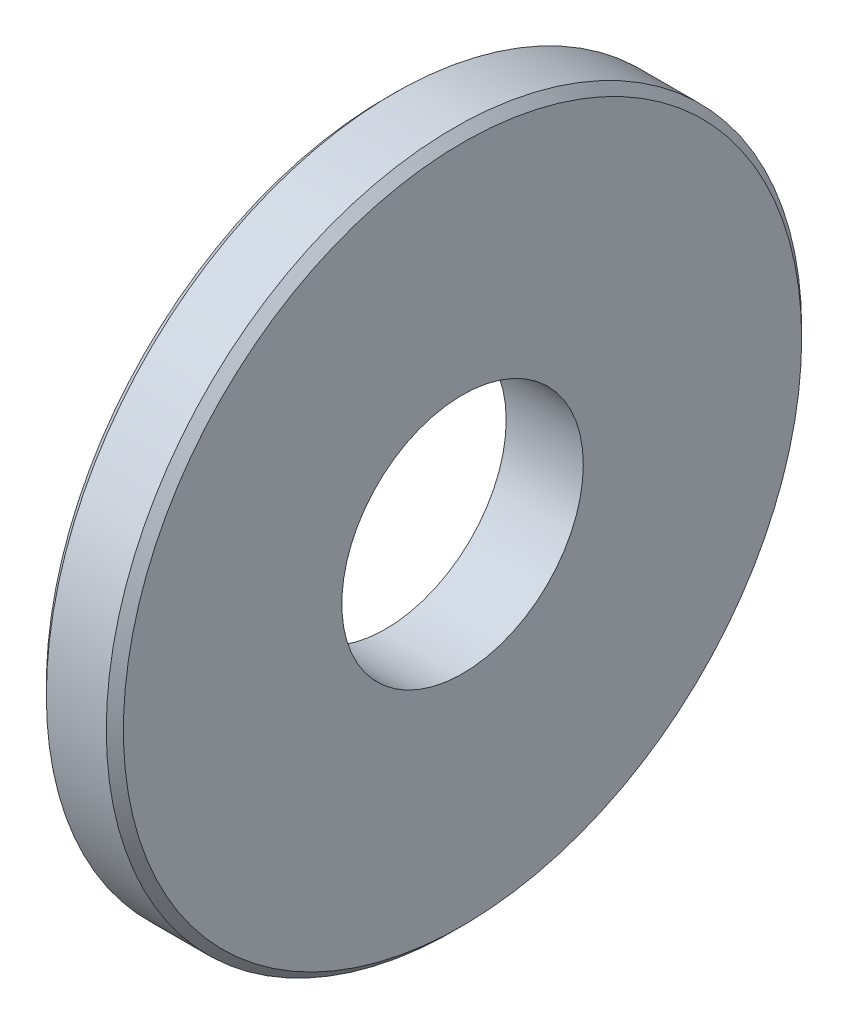
SolidWorks part; units mm, degrees
ref_plane "Front Plane" through (0, 0, 0) normal (0, 0, 1) x (1, 0, 0)
ref_plane "Top Plane" through (0, 0, 0) normal (0, 1, 0) x (1, 0, 0)
ref_plane "Right Plane" through (0, 0, 0) normal (1, 0, 0) x (0, 0, -1)
sketch "Sketch1" plane through (0, 0, 0) normal (1, 0, 0) x (0, 0, -1)
  circle A0 centre (0, 0) radius 5.1562
  circle A1 centre (0, 0) radius 1.7907
  dimension "D1" = 10.3124
  dimension "D2" = 3.5814
extrude "Boss-Extrude1" add sketch "Sketch1" along normal blind 1.143
chamfer "Chamfer1" distance 0.127 angle 45 2 edges at (1.143, 0, -5.1562) (0, 0, -5.1562)
